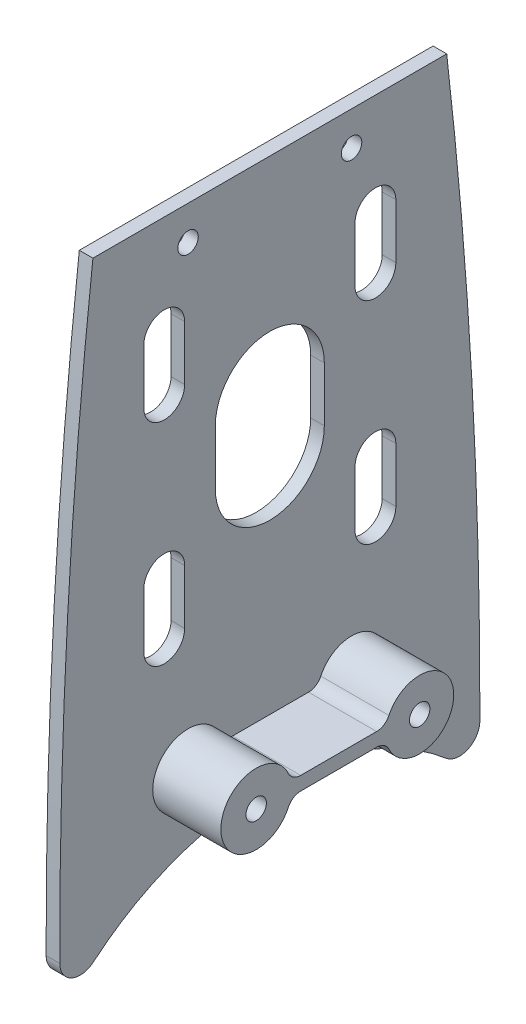
SolidWorks part; units mm, degrees
ref_plane "Front Plane" through (0, 0, 0) normal (0, 0, 1) x (1, 0, 0)
ref_plane "Top Plane" through (0, 0, 0) normal (0, 1, 0) x (1, 0, 0)
ref_plane "Right Plane" through (0, 0, 0) normal (1, 0, 0) x (0, 0, -1)
sketch "Sketch1" plane through (0, 0, 0) normal (1, 0, 0) x (0, 0, -1)
  line L0 (-25.9681, 120) -> (25.9681, 120)
  line L1 (-12, 115) -> (12, 115) construction
  line L2 (-12, 48) -> (12, 48) construction
  line L3 (0, 89.7) -> (0, 81.7) construction
  line L4 (8, 89.7) -> (8, 81.7)
  line L5 (-8, 89.7) -> (-8, 81.7)
  line L6 (15.5, 105.2) -> (15.5, 97.2) construction
  line L7 (18.5, 105.2) -> (18.5, 97.2)
  line L8 (12.5, 105.2) -> (12.5, 97.2)
  line L9 (15.5, 74.2) -> (15.5, 66.2) construction
  line L10 (18.5, 74.2) -> (18.5, 66.2)
  line L11 (12.5, 74.2) -> (12.5, 66.2)
  line L12 (-15.5, 105.2) -> (-15.5, 97.2) construction
  line L13 (-12.5, 105.2) -> (-12.5, 97.2)
  line L14 (-18.5, 105.2) -> (-18.5, 97.2)
  line L15 (-15.5, 74.2) -> (-15.5, 66.2) construction
  line L16 (-12.5, 74.2) -> (-12.5, 66.2)
  line L17 (-18.5, 74.2) -> (-18.5, 66.2)
  line L18 (15.5, 101.2) -> (-15.5, 70.2) construction
  arc A0 (-29.9652, -1.4453) -> (29.9652, -1.4453) centre (0, 0) ccw construction
  arc A1 (-19.7031, 163.4332) -> (19.7031, 163.4332) centre (0, 160) cw construction
  arc A2 (-29.9652, -1.4453) -> (-19.7031, 163.4332) centre (719.1639, 34.6875) cw construction
  arc A3 (29.9652, -1.4453) -> (19.7031, 163.4332) centre (-719.1639, 34.6875) ccw construction
  arc A4 (-25.8917, 30.4896) -> (25.8917, 30.4896) centre (0, 0) cw
  arc A5 (-30.8336, 32.7687) -> (-25.9681, 120) centre (719.1639, 34.6875) cw
  arc A6 (25.9681, 120) -> (30.8336, 32.7687) centre (-719.1639, 34.6875) cw
  circle A7 centre (-12, 115) radius 1.5
  circle A8 centre (12, 115) radius 1.5
  circle A9 centre (-12, 48) radius 1.5
  circle A10 centre (12, 48) radius 1.5
  arc A11 (8, 89.7) -> (-8, 89.7) centre (0, 89.7) ccw
  arc A12 (-8, 81.7) -> (8, 81.7) centre (0, 81.7) ccw
  arc A13 (18.5, 105.2) -> (12.5, 105.2) centre (15.5, 105.2) ccw
  arc A14 (12.5, 97.2) -> (18.5, 97.2) centre (15.5, 97.2) ccw
  arc A15 (18.5, 74.2) -> (12.5, 74.2) centre (15.5, 74.2) ccw
  arc A16 (12.5, 66.2) -> (18.5, 66.2) centre (15.5, 66.2) ccw
  arc A17 (-12.5, 105.2) -> (-18.5, 105.2) centre (-15.5, 105.2) ccw
  arc A18 (-18.5, 97.2) -> (-12.5, 97.2) centre (-15.5, 97.2) ccw
  arc A19 (-12.5, 74.2) -> (-18.5, 74.2) centre (-15.5, 74.2) ccw
  arc A20 (-18.5, 66.2) -> (-12.5, 66.2) centre (-15.5, 66.2) ccw
  arc A21 (25.8917, 30.4896) -> (30.8336, 32.7687) centre (27.8336, 32.7764) ccw
  arc A22 (-25.8917, 30.4896) -> (-30.8336, 32.7687) centre (-27.8336, 32.7764) cw
  point P21 (0, 115)
  point P22 (0, 48)
  point P27 (0, 85.7)
  point P33 (15.5, 101.2)
  point P40 (15.5, 70.2)
  point P47 (-15.5, 101.2)
  point P54 (-15.5, 70.2)
  point P61 (-12.5, 70.2)
  point P80 (0, 85.7)
  point P83 (30.7803, 25.5455)
  point P86 (-30.7803, 25.5455)
  dimension "D1" = 30
  dimension "D2" = 20
  dimension "D4" = 750
  dimension "D5" = 750
  dimension "D6" = 40
  dimension "D8" = 3
  dimension "D9" = 3
  dimension "D10" = 3
  dimension "D11" = 3
  dimension "D29" = 3
  dimension "D3" = 160
  dimension "D7" = 40
  dimension "D12" = 24
  dimension "D13" = 24
  dimension "D14" = 45
  dimension "D15" = 48
  dimension "D16" = 8
  dimension "D17" = 16
  dimension "D18" = 74.3
  dimension "D19" = 8
  dimension "D20" = 6
  dimension "D21" = 8
  dimension "D22" = 6
  dimension "D23" = 6
  dimension "D24" = 8
  dimension "D25" = 8
  dimension "D26" = 6
  dimension "D27" = 31
  dimension "D28" = 31
extrude "Boss-Extrude1" add sketch "Sketch1" along normal blind 2
sketch "Sketch2" plane through (2, 0, 0) normal (1, 0, 0) x (0, 0, -1)
  line L0 (-6.9104, 49) -> (7.101, 49)
  line L1 (-6.9104, 47) -> (7.101, 47)
  line L2 (-6.9104, 49) -> (-6.9104, 47) construction
  circle A0 centre (-12, 48) radius 1.5
  circle A2 centre (12, 48) radius 1.5
  circle A4 centre (-12, 48) radius 1.5 construction
  circle A5 centre (12, 48) radius 1.5 construction
  arc A6 (-6.9104, 49) -> (-6.9104, 47) centre (-12, 48) ccw
  arc A7 (7.101, 49) -> (7.101, 47) centre (12, 48) cw
  point P14 (-6.9104, 48)
  dimension "D1" = 5
  dimension "D2" = 5.1869
  dimension "D3" = 2
extrude "Boss-Extrude2" add sketch "Sketch2" along normal blind 10
fillet "Fillet1" radius 2 4 edges at (7, 49, -7.101) (7, 49, 6.9104) (7, 47, -7.101) (7, 47, 6.9104)
